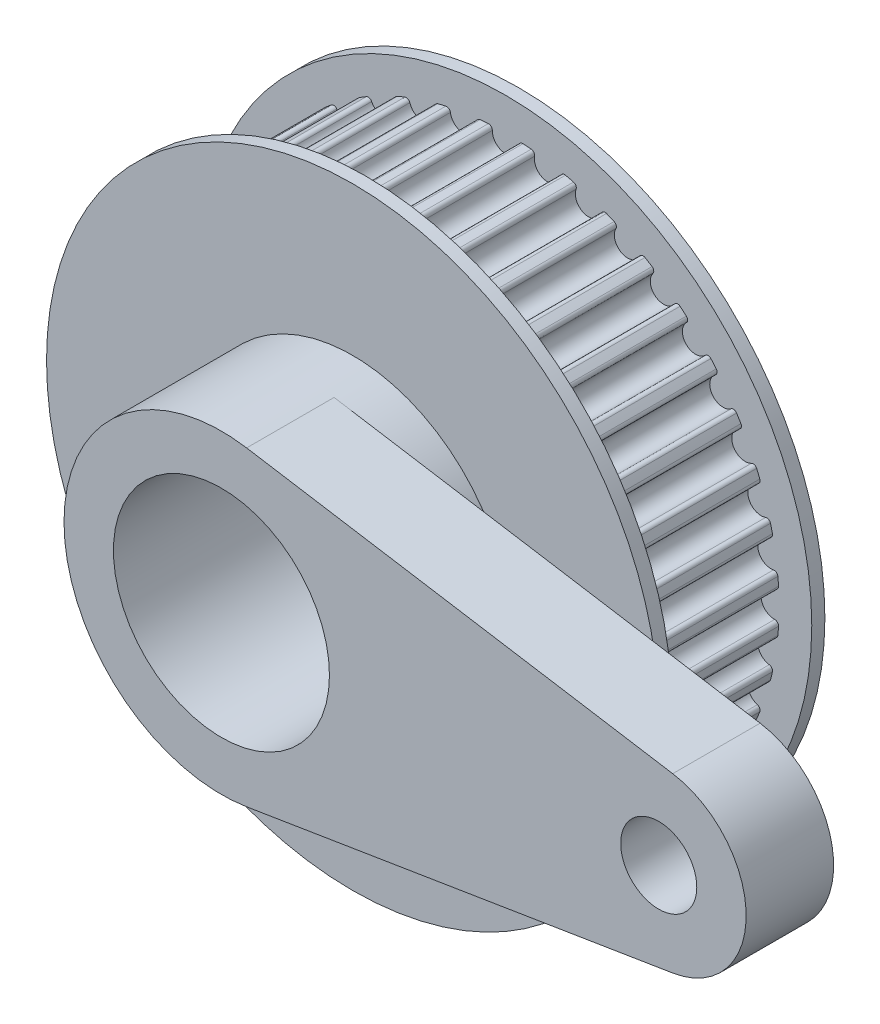
SolidWorks part; units mm, degrees
ref_plane "Front Plane" through (0, 0, 0) normal (0, 0, 1) x (1, 0, 0)
ref_plane "Top Plane" through (0, 0, 0) normal (0, 1, 0) x (1, 0, 0)
ref_plane "Right Plane" through (0, 0, 0) normal (1, 0, 0) x (0, 0, -1)
sketch "Sketch2" plane through (0, 0, 0) normal (0, 0, 1) x (1, 0, 0)
  line L0 (-22.12, 17.7681) -> (26.6, 9.8712)
  line L1 (-22.12, -17.7681) -> (26.6, -9.8712)
  arc A0 (-22.12, 17.7681) -> (-22.12, -17.7681) centre (-25, 0) ccw
  arc A1 (26.6, -9.8712) -> (26.6, 9.8712) centre (25, 0) ccw
  dimension "D1" = 36
  dimension "D2" = 20
  dimension "D3" = 50
  dimension "D4" = 25
extrude "Boss-Extrude1" add sketch "Sketch2" along normal blind 15
sketch "Sketch3" plane through (0, 0, 15) normal (0, 0, 1) x (1, 0, 0)
  circle A0 centre (-25, 0) radius 12.35
  circle A2 centre (25, 0) radius 4.35
  dimension "D1" = 24.7
  dimension "D2" = 8.7
extrude "Cut-Extrude1" cut sketch "Sketch3" against normal through all
sketch "Sketch4" plane through (0, 0, 0) normal (0, 0, -1) x (-1, 0, 0)
  line L0 (22.12, 17.7681) -> (-26.6, 9.8712)
  line L1 (-26.6, -9.8712) -> (22.12, -17.7681)
  arc A0 (22.12, 17.7681) -> (22.12, -17.7681) centre (25, 0) ccw
  arc A1 (-26.6, 9.8712) -> (-26.6, -9.8712) centre (-25, 0) ccw
extrude "Cut-Extrude2" cut sketch "Sketch4" against normal blind 5
sketch "Sketch5" plane through (0, 0, 15) normal (0, 0, 1) x (1, 0, 0)
  arc A2 (-25, 29.2) -> (-23.4754, 30.7585) centre (-25, 30.725) ccw
  arc A3 (-23.0182, 31.1971) -> (-23.4754, 30.7585) centre (-23.0455, 30.768) ccw
  arc A4 (-21.6942, 30.6183) -> (-20.4321, 28.8405) centre (-20.1936, 30.3467) ccw
  arc A5 (-21.6942, 30.6183) -> (-22.0771, 31.123) centre (-22.1173, 30.6949) ccw
  arc A6 (-22.0771, 31.123) -> (-23.0182, 31.1971) centre (-25, 0) ccw
  arc A7 (-20.4321, 28.8405) -> (-18.6824, 30.1413) centre (-20.1936, 30.3467) ccw
  arc A8 (-18.1623, 30.503) -> (-18.6824, 30.1413) centre (-18.2564, 30.0834) ccw
  arc A9 (-17.2444, 30.2826) -> (-18.1623, 30.503) centre (-25, 0) ccw
  arc A10 (-16.9451, 29.7242) -> (-17.2444, 30.2826) centre (-17.351, 29.8661) ccw
  arc A11 (-16.9451, 29.7242) -> (-15.9767, 27.7709) centre (-15.5055, 29.2212) ccw
  arc A12 (-15.9767, 27.7709) -> (-14.0451, 28.782) centre (-15.5055, 29.2212) ccw
  arc A13 (-13.4748, 29.0578) -> (-14.0451, 28.782) centre (-13.6333, 28.6581) ccw
  arc A14 (-12.6026, 28.6965) -> (-13.4748, 29.0578) centre (-25, 0) ccw
  arc A15 (-12.3944, 28.0982) -> (-12.6026, 28.6965) centre (-12.7731, 28.3018) ccw
  arc A16 (-12.3944, 28.0982) -> (-11.7435, 26.0174) centre (-11.0511, 27.3762) ccw
  arc A17 (-11.7435, 26.0174) -> (-9.6775, 26.7139) centre (-11.0511, 27.3762) ccw
  arc A18 (-9.071, 26.8971) -> (-9.6775, 26.7139) centre (-9.2901, 26.5271) ccw
  arc A19 (-8.2661, 26.4039) -> (-9.071, 26.8971) centre (-25, 0) ccw
  arc A20 (-8.154, 25.7803) -> (-8.2661, 26.4039) centre (-8.4963, 26.0407) ccw
  arc A21 (-8.154, 25.7803) -> (-7.8367, 23.6233) centre (-6.9403, 24.857) ccw
  arc A22 (-7.8367, 23.6233) -> (-5.6871, 23.988) centre (-6.9403, 24.857) ccw
  arc A23 (-5.0595, 24.0741) -> (-5.6871, 23.988) centre (-5.3338, 23.743) ccw
  arc A24 (-4.3416, 23.461) -> (-5.0595, 24.0741) centre (-25, 0) ccw
  arc A25 (-4.3285, 22.8276) -> (-4.3416, 23.461) centre (-4.6258, 23.1383) ccw
  arc A26 (-4.3285, 22.8276) -> (-4.3525, 20.6475) centre (-3.2741, 21.7259) ccw
  arc A27 (-4.3525, 20.6475) -> (-2.1724, 20.6715) centre (-3.2741, 21.7259) ccw
  arc A28 (-1.539, 20.6584) -> (-2.1724, 20.6715) centre (-1.8617, 20.3742) ccw
  arc A29 (-0.9259, 19.9405) -> (-1.539, 20.6584) centre (-25, 0) ccw
  arc A30 (-1.012, 19.3129) -> (-0.9259, 19.9405) centre (-1.257, 19.6662) ccw
  arc A31 (-1.012, 19.3129) -> (-1.3767, 17.1633) centre (-0.143, 18.0597) ccw
  arc A32 (-1.3767, 17.1633) -> (0.7803, 16.846) centre (-0.143, 18.0597) ccw
  arc A33 (1.4039, 16.7339) -> (0.7803, 16.846) centre (1.0407, 16.5037) ccw
  arc A34 (1.8971, 15.929) -> (1.4039, 16.7339) centre (-25, 0) ccw
  arc A35 (1.7139, 15.3225) -> (1.8971, 15.929) centre (1.5271, 15.7099) ccw
  arc A36 (1.7139, 15.3225) -> (1.0174, 13.2565) centre (2.3762, 13.9489) ccw
  arc A37 (1.0174, 13.2565) -> (3.0982, 12.6056) centre (2.3762, 13.9489) ccw
  arc A38 (3.6965, 12.3974) -> (3.0982, 12.6056) centre (3.3018, 12.2269) ccw
  arc A39 (4.0578, 11.5252) -> (3.6965, 12.3974) centre (-25, 0) ccw
  arc A40 (3.782, 10.9549) -> (4.0578, 11.5252) centre (3.6581, 11.3667) ccw
  arc A41 (3.782, 10.9549) -> (2.7709, 9.0233) centre (4.2212, 9.4945) ccw
  arc A42 (2.7709, 9.0233) -> (4.7242, 8.0549) centre (4.2212, 9.4945) ccw
  arc A43 (5.2826, 7.7556) -> (4.7242, 8.0549) centre (4.8661, 7.649) ccw
  arc A44 (5.503, 6.8377) -> (5.2826, 7.7556) centre (-25, 0) ccw
  arc A45 (5.1413, 6.3176) -> (5.503, 6.8377) centre (5.0834, 6.7436) ccw
  arc A46 (5.1413, 6.3176) -> (3.8405, 4.5679) centre (5.3467, 4.8064) ccw
  arc A47 (3.8405, 4.5679) -> (5.6183, 3.3058) centre (5.3467, 4.8064) ccw
  arc A48 (6.123, 2.9229) -> (5.6183, 3.3058) centre (5.6949, 2.8827) ccw
  arc A49 (6.1971, 1.9818) -> (6.123, 2.9229) centre (-25, 0) ccw
  arc A50 (5.7585, 1.5246) -> (6.1971, 1.9818) centre (5.768, 1.9545) ccw
  arc A51 (5.7585, 1.5246) -> (4.2, 0) centre (5.725, 0) ccw
  arc A52 (4.2, 0) -> (5.7585, -1.5246) centre (5.725, 0) ccw
  arc A53 (6.1971, -1.9818) -> (5.7585, -1.5246) centre (5.768, -1.9545) ccw
  arc A54 (6.123, -2.9229) -> (6.1971, -1.9818) centre (-25, 0) ccw
  arc A55 (5.6183, -3.3058) -> (6.123, -2.9229) centre (5.6949, -2.8827) ccw
  arc A56 (5.6183, -3.3058) -> (3.8405, -4.5679) centre (5.3467, -4.8064) ccw
  arc A57 (3.8405, -4.5679) -> (5.1413, -6.3176) centre (5.3467, -4.8064) ccw
  arc A58 (5.503, -6.8377) -> (5.1413, -6.3176) centre (5.0834, -6.7436) ccw
  arc A59 (5.2826, -7.7556) -> (5.503, -6.8377) centre (-25, 0) ccw
  arc A60 (4.7242, -8.0549) -> (5.2826, -7.7556) centre (4.8661, -7.649) ccw
  arc A61 (4.7242, -8.0549) -> (2.7709, -9.0233) centre (4.2212, -9.4945) ccw
  arc A62 (2.7709, -9.0233) -> (3.782, -10.9549) centre (4.2212, -9.4945) ccw
  arc A63 (4.0578, -11.5252) -> (3.782, -10.9549) centre (3.6581, -11.3667) ccw
  arc A64 (3.6965, -12.3974) -> (4.0578, -11.5252) centre (-25, 0) ccw
  arc A65 (3.0982, -12.6056) -> (3.6965, -12.3974) centre (3.3018, -12.2269) ccw
  arc A66 (3.0982, -12.6056) -> (1.0174, -13.2565) centre (2.3762, -13.9489) ccw
  arc A67 (1.0174, -13.2565) -> (1.7139, -15.3225) centre (2.3762, -13.9489) ccw
  arc A68 (1.8971, -15.929) -> (1.7139, -15.3225) centre (1.5271, -15.7099) ccw
  arc A69 (1.4039, -16.7339) -> (1.8971, -15.929) centre (-25, 0) ccw
  arc A70 (0.7803, -16.846) -> (1.4039, -16.7339) centre (1.0407, -16.5037) ccw
  arc A71 (0.7803, -16.846) -> (-1.3767, -17.1633) centre (-0.143, -18.0597) ccw
  arc A72 (-1.3767, -17.1633) -> (-1.012, -19.3129) centre (-0.143, -18.0597) ccw
  arc A73 (-0.9259, -19.9405) -> (-1.012, -19.3129) centre (-1.257, -19.6662) ccw
  arc A74 (-1.539, -20.6584) -> (-0.9259, -19.9405) centre (-25, 0) ccw
  arc A75 (-2.1724, -20.6715) -> (-1.539, -20.6584) centre (-1.8617, -20.3742) ccw
  arc A76 (-2.1724, -20.6715) -> (-4.3525, -20.6475) centre (-3.2741, -21.7259) ccw
  arc A77 (-4.3525, -20.6475) -> (-4.3285, -22.8276) centre (-3.2741, -21.7259) ccw
  arc A78 (-4.3416, -23.461) -> (-4.3285, -22.8276) centre (-4.6258, -23.1383) ccw
  arc A79 (-5.0595, -24.0741) -> (-4.3416, -23.461) centre (-25, 0) ccw
  arc A80 (-5.6871, -23.988) -> (-5.0595, -24.0741) centre (-5.3338, -23.743) ccw
  arc A81 (-5.6871, -23.988) -> (-7.8367, -23.6233) centre (-6.9403, -24.857) ccw
  arc A82 (-7.8367, -23.6233) -> (-8.154, -25.7803) centre (-6.9403, -24.857) ccw
  arc A83 (-8.2661, -26.4039) -> (-8.154, -25.7803) centre (-8.4963, -26.0407) ccw
  arc A84 (-9.071, -26.8971) -> (-8.2661, -26.4039) centre (-25, 0) ccw
  arc A85 (-9.6775, -26.7139) -> (-9.071, -26.8971) centre (-9.2901, -26.5271) ccw
  arc A86 (-9.6775, -26.7139) -> (-11.7435, -26.0174) centre (-11.0511, -27.3762) ccw
  arc A87 (-11.7435, -26.0174) -> (-12.3944, -28.0982) centre (-11.0511, -27.3762) ccw
  arc A88 (-12.6026, -28.6965) -> (-12.3944, -28.0982) centre (-12.7731, -28.3018) ccw
  arc A89 (-13.4748, -29.0578) -> (-12.6026, -28.6965) centre (-25, 0) ccw
  arc A90 (-14.0451, -28.782) -> (-13.4748, -29.0578) centre (-13.6333, -28.6581) ccw
  arc A91 (-14.0451, -28.782) -> (-15.9767, -27.7709) centre (-15.5055, -29.2212) ccw
  arc A92 (-15.9767, -27.7709) -> (-16.9451, -29.7242) centre (-15.5055, -29.2212) ccw
  arc A93 (-17.2444, -30.2826) -> (-16.9451, -29.7242) centre (-17.351, -29.8661) ccw
  arc A94 (-18.1623, -30.503) -> (-17.2444, -30.2826) centre (-25, 0) ccw
  arc A95 (-18.6824, -30.1413) -> (-18.1623, -30.503) centre (-18.2564, -30.0834) ccw
  arc A96 (-18.6824, -30.1413) -> (-20.4321, -28.8405) centre (-20.1936, -30.3467) ccw
  arc A97 (-20.4321, -28.8405) -> (-21.6942, -30.6183) centre (-20.1936, -30.3467) ccw
  arc A98 (-22.0771, -31.123) -> (-21.6942, -30.6183) centre (-22.1173, -30.6949) ccw
  arc A99 (-23.0182, -31.1971) -> (-22.0771, -31.123) centre (-25, 0) ccw
  arc A100 (-23.4754, -30.7585) -> (-23.0182, -31.1971) centre (-23.0455, -30.768) ccw
  arc A101 (-23.4754, -30.7585) -> (-25, -29.2) centre (-25, -30.725) ccw
  arc A102 (-25, -29.2) -> (-26.5246, -30.7585) centre (-25, -30.725) ccw
  arc A103 (-26.9818, -31.1971) -> (-26.5246, -30.7585) centre (-26.9545, -30.768) ccw
  arc A104 (-27.9229, -31.123) -> (-26.9818, -31.1971) centre (-25, 0) ccw
  arc A105 (-28.3058, -30.6183) -> (-27.9229, -31.123) centre (-27.8827, -30.6949) ccw
  arc A106 (-28.3058, -30.6183) -> (-29.5679, -28.8405) centre (-29.8064, -30.3467) ccw
  arc A107 (-29.5679, -28.8405) -> (-31.3176, -30.1413) centre (-29.8064, -30.3467) ccw
  arc A108 (-31.8377, -30.503) -> (-31.3176, -30.1413) centre (-31.7436, -30.0834) ccw
  arc A109 (-32.7556, -30.2826) -> (-31.8377, -30.503) centre (-25, 0) ccw
  arc A110 (-33.0549, -29.7242) -> (-32.7556, -30.2826) centre (-32.649, -29.8661) ccw
  arc A111 (-33.0549, -29.7242) -> (-34.0233, -27.7709) centre (-34.4945, -29.2212) ccw
  arc A112 (-34.0233, -27.7709) -> (-35.9549, -28.782) centre (-34.4945, -29.2212) ccw
  arc A113 (-36.5252, -29.0578) -> (-35.9549, -28.782) centre (-36.3667, -28.6581) ccw
  arc A114 (-37.3974, -28.6965) -> (-36.5252, -29.0578) centre (-25, 0) ccw
  arc A115 (-37.6056, -28.0982) -> (-37.3974, -28.6965) centre (-37.2269, -28.3018) ccw
  arc A116 (-37.6056, -28.0982) -> (-38.2565, -26.0174) centre (-38.9489, -27.3762) ccw
  arc A117 (-38.2565, -26.0174) -> (-40.3225, -26.7139) centre (-38.9489, -27.3762) ccw
  arc A118 (-40.929, -26.8971) -> (-40.3225, -26.7139) centre (-40.7099, -26.5271) ccw
  arc A119 (-41.7339, -26.4039) -> (-40.929, -26.8971) centre (-25, 0) ccw
  arc A120 (-41.846, -25.7803) -> (-41.7339, -26.4039) centre (-41.5037, -26.0407) ccw
  arc A121 (-41.846, -25.7803) -> (-42.1633, -23.6233) centre (-43.0597, -24.857) ccw
  arc A122 (-42.1633, -23.6233) -> (-44.3129, -23.988) centre (-43.0597, -24.857) ccw
  arc A123 (-44.9405, -24.0741) -> (-44.3129, -23.988) centre (-44.6662, -23.743) ccw
  arc A124 (-45.6584, -23.461) -> (-44.9405, -24.0741) centre (-25, 0) ccw
  arc A125 (-45.6715, -22.8276) -> (-45.6584, -23.461) centre (-45.3742, -23.1383) ccw
  arc A126 (-45.6715, -22.8276) -> (-45.6475, -20.6475) centre (-46.7259, -21.7259) ccw
  arc A127 (-45.6475, -20.6475) -> (-47.8276, -20.6715) centre (-46.7259, -21.7259) ccw
  arc A128 (-48.461, -20.6584) -> (-47.8276, -20.6715) centre (-48.1383, -20.3742) ccw
  arc A129 (-49.0741, -19.9405) -> (-48.461, -20.6584) centre (-25, 0) ccw
  arc A130 (-48.988, -19.3129) -> (-49.0741, -19.9405) centre (-48.743, -19.6662) ccw
  arc A131 (-48.988, -19.3129) -> (-48.6233, -17.1633) centre (-49.857, -18.0597) ccw
  arc A132 (-48.6233, -17.1633) -> (-50.7803, -16.846) centre (-49.857, -18.0597) ccw
  arc A133 (-51.4039, -16.7339) -> (-50.7803, -16.846) centre (-51.0407, -16.5037) ccw
  arc A134 (-51.8971, -15.929) -> (-51.4039, -16.7339) centre (-25, 0) ccw
  arc A135 (-51.7139, -15.3225) -> (-51.8971, -15.929) centre (-51.5271, -15.7099) ccw
  arc A136 (-51.7139, -15.3225) -> (-51.0174, -13.2565) centre (-52.3762, -13.9489) ccw
  arc A137 (-51.0174, -13.2565) -> (-53.0982, -12.6056) centre (-52.3762, -13.9489) ccw
  arc A138 (-53.6965, -12.3974) -> (-53.0982, -12.6056) centre (-53.3018, -12.2269) ccw
  arc A139 (-54.0578, -11.5252) -> (-53.6965, -12.3974) centre (-25, 0) ccw
  arc A140 (-53.782, -10.9549) -> (-54.0578, -11.5252) centre (-53.6581, -11.3667) ccw
  arc A141 (-53.782, -10.9549) -> (-52.7709, -9.0233) centre (-54.2212, -9.4945) ccw
  arc A142 (-52.7709, -9.0233) -> (-54.7242, -8.0549) centre (-54.2212, -9.4945) ccw
  arc A143 (-55.2826, -7.7556) -> (-54.7242, -8.0549) centre (-54.8661, -7.649) ccw
  arc A144 (-55.503, -6.8377) -> (-55.2826, -7.7556) centre (-25, 0) ccw
  arc A145 (-55.1413, -6.3176) -> (-55.503, -6.8377) centre (-55.0834, -6.7436) ccw
  arc A146 (-55.1413, -6.3176) -> (-53.8405, -4.5679) centre (-55.3467, -4.8064) ccw
  arc A147 (-53.8405, -4.5679) -> (-55.6183, -3.3058) centre (-55.3467, -4.8064) ccw
  arc A148 (-56.123, -2.9229) -> (-55.6183, -3.3058) centre (-55.6949, -2.8827) ccw
  arc A149 (-56.1971, -1.9818) -> (-56.123, -2.9229) centre (-25, 0) ccw
  arc A150 (-55.7585, -1.5246) -> (-56.1971, -1.9818) centre (-55.768, -1.9545) ccw
  arc A151 (-55.7585, -1.5246) -> (-54.2, 0) centre (-55.725, 0) ccw
  arc A152 (-54.2, 0) -> (-55.7585, 1.5246) centre (-55.725, 0) ccw
  arc A153 (-56.1971, 1.9818) -> (-55.7585, 1.5246) centre (-55.768, 1.9545) ccw
  arc A154 (-56.123, 2.9229) -> (-56.1971, 1.9818) centre (-25, 0) ccw
  arc A155 (-55.6183, 3.3058) -> (-56.123, 2.9229) centre (-55.6949, 2.8827) ccw
  arc A156 (-55.6183, 3.3058) -> (-53.8405, 4.5679) centre (-55.3467, 4.8064) ccw
  arc A157 (-53.8405, 4.5679) -> (-55.1413, 6.3176) centre (-55.3467, 4.8064) ccw
  arc A158 (-55.503, 6.8377) -> (-55.1413, 6.3176) centre (-55.0834, 6.7436) ccw
  arc A159 (-55.2826, 7.7556) -> (-55.503, 6.8377) centre (-25, 0) ccw
  arc A160 (-54.7242, 8.0549) -> (-55.2826, 7.7556) centre (-54.8661, 7.649) ccw
  arc A161 (-54.7242, 8.0549) -> (-52.7709, 9.0233) centre (-54.2212, 9.4945) ccw
  arc A162 (-52.7709, 9.0233) -> (-53.782, 10.9549) centre (-54.2212, 9.4945) ccw
  arc A163 (-54.0578, 11.5252) -> (-53.782, 10.9549) centre (-53.6581, 11.3667) ccw
  arc A164 (-53.6965, 12.3974) -> (-54.0578, 11.5252) centre (-25, 0) ccw
  arc A165 (-53.0982, 12.6056) -> (-53.6965, 12.3974) centre (-53.3018, 12.2269) ccw
  arc A166 (-53.0982, 12.6056) -> (-51.0174, 13.2565) centre (-52.3762, 13.9489) ccw
  arc A167 (-51.0174, 13.2565) -> (-51.7139, 15.3225) centre (-52.3762, 13.9489) ccw
  arc A168 (-51.8971, 15.929) -> (-51.7139, 15.3225) centre (-51.5271, 15.7099) ccw
  arc A169 (-51.4039, 16.7339) -> (-51.8971, 15.929) centre (-25, 0) ccw
  arc A170 (-50.7803, 16.846) -> (-51.4039, 16.7339) centre (-51.0407, 16.5037) ccw
  arc A171 (-50.7803, 16.846) -> (-48.6233, 17.1633) centre (-49.857, 18.0597) ccw
  arc A172 (-48.6233, 17.1633) -> (-48.988, 19.3129) centre (-49.857, 18.0597) ccw
  arc A173 (-49.0741, 19.9405) -> (-48.988, 19.3129) centre (-48.743, 19.6662) ccw
  arc A174 (-48.461, 20.6584) -> (-49.0741, 19.9405) centre (-25, 0) ccw
  arc A175 (-47.8276, 20.6715) -> (-48.461, 20.6584) centre (-48.1383, 20.3742) ccw
  arc A176 (-47.8276, 20.6715) -> (-45.6475, 20.6475) centre (-46.7259, 21.7259) ccw
  arc A177 (-45.6475, 20.6475) -> (-45.6715, 22.8276) centre (-46.7259, 21.7259) ccw
  arc A178 (-45.6584, 23.461) -> (-45.6715, 22.8276) centre (-45.3742, 23.1383) ccw
  arc A179 (-44.9405, 24.0741) -> (-45.6584, 23.461) centre (-25, 0) ccw
  arc A180 (-44.3129, 23.988) -> (-44.9405, 24.0741) centre (-44.6662, 23.743) ccw
  arc A181 (-44.3129, 23.988) -> (-42.1633, 23.6233) centre (-43.0597, 24.857) ccw
  arc A182 (-42.1633, 23.6233) -> (-41.846, 25.7803) centre (-43.0597, 24.857) ccw
  arc A183 (-41.7339, 26.4039) -> (-41.846, 25.7803) centre (-41.5037, 26.0407) ccw
  arc A184 (-40.929, 26.8971) -> (-41.7339, 26.4039) centre (-25, 0) ccw
  arc A185 (-40.3225, 26.7139) -> (-40.929, 26.8971) centre (-40.7099, 26.5271) ccw
  arc A186 (-40.3225, 26.7139) -> (-38.2565, 26.0174) centre (-38.9489, 27.3762) ccw
  arc A187 (-38.2565, 26.0174) -> (-37.6056, 28.0982) centre (-38.9489, 27.3762) ccw
  arc A188 (-37.3974, 28.6965) -> (-37.6056, 28.0982) centre (-37.2269, 28.3018) ccw
  arc A189 (-36.5252, 29.0578) -> (-37.3974, 28.6965) centre (-25, 0) ccw
  arc A190 (-35.9549, 28.782) -> (-36.5252, 29.0578) centre (-36.3667, 28.6581) ccw
  arc A191 (-35.9549, 28.782) -> (-34.0233, 27.7709) centre (-34.4945, 29.2212) ccw
  arc A192 (-34.0233, 27.7709) -> (-33.0549, 29.7242) centre (-34.4945, 29.2212) ccw
  arc A193 (-32.7556, 30.2826) -> (-33.0549, 29.7242) centre (-32.649, 29.8661) ccw
  arc A194 (-31.8377, 30.503) -> (-32.7556, 30.2826) centre (-25, 0) ccw
  arc A195 (-31.3176, 30.1413) -> (-31.8377, 30.503) centre (-31.7436, 30.0834) ccw
  arc A196 (-31.3176, 30.1413) -> (-29.5679, 28.8405) centre (-29.8064, 30.3467) ccw
  arc A197 (-29.5679, 28.8405) -> (-28.3058, 30.6183) centre (-29.8064, 30.3467) ccw
  arc A198 (-27.9229, 31.123) -> (-28.3058, 30.6183) centre (-27.8827, 30.6949) ccw
  arc A199 (-26.9818, 31.1971) -> (-27.9229, 31.123) centre (-25, 0) ccw
  arc A200 (-26.5246, 30.7585) -> (-26.9818, 31.1971) centre (-26.9545, 30.768) ccw
  arc A201 (-26.5246, 30.7585) -> (-25, 29.2) centre (-25, 30.725) ccw
  point P407 (-25, 0)
  dimension "D1" = 40
  dimension "D4" = 3.05
  dimension "D5" = 0.86
  dimension "D6" = 3.05
  dimension "D7" = 0.86
sketch "Sketch6" plane through (0, 0, 0) normal (0, 0, -1) x (-1, 0, 0)
  circle A0 centre (25, 0) radius 35
  dimension "D1" = 70
extrude "Boss-Extrude2" add sketch "Sketch6" along normal blind 1.5
sketch "Sketch7" plane through (0, 0, -1.5) normal (0, 0, -1) x (-1, 0, 0)
  circle A1 centre (25, 0) radius 35
  circle A2 centre (25, 0) radius 35
  arc A202 (47.8276, -20.6715) -> (45.6475, -20.6475) centre (46.7259, -21.7259) ccw
  arc A203 (47.8276, -20.6715) -> (48.461, -20.6584) centre (48.1383, -20.3742) ccw
  arc A204 (48.461, -20.6584) -> (49.0741, -19.9405) centre (25, 0) ccw
  arc A205 (49.0741, -19.9405) -> (48.988, -19.3129) centre (48.743, -19.6662) ccw
  arc A206 (48.6233, -17.1633) -> (48.988, -19.3129) centre (49.857, -18.0597) ccw
  arc A207 (50.7803, -16.846) -> (48.6233, -17.1633) centre (49.857, -18.0597) ccw
  arc A208 (50.7803, -16.846) -> (51.4039, -16.7339) centre (51.0407, -16.5037) ccw
  arc A209 (51.4039, -16.7339) -> (51.8971, -15.929) centre (25, 0) ccw
  arc A210 (51.8971, -15.929) -> (51.7139, -15.3225) centre (51.5271, -15.7099) ccw
  arc A211 (51.0174, -13.2565) -> (51.7139, -15.3225) centre (52.3762, -13.9489) ccw
  arc A212 (53.0982, -12.6056) -> (51.0174, -13.2565) centre (52.3762, -13.9489) ccw
  arc A213 (53.0982, -12.6056) -> (53.6965, -12.3974) centre (53.3018, -12.2269) ccw
  arc A214 (53.6965, -12.3974) -> (54.0578, -11.5252) centre (25, 0) ccw
  arc A215 (54.0578, -11.5252) -> (53.782, -10.9549) centre (53.6581, -11.3667) ccw
  arc A216 (52.7709, -9.0233) -> (53.782, -10.9549) centre (54.2212, -9.4945) ccw
  arc A217 (54.7242, -8.0549) -> (52.7709, -9.0233) centre (54.2212, -9.4945) ccw
  arc A218 (54.7242, -8.0549) -> (55.2826, -7.7556) centre (54.8661, -7.649) ccw
  arc A219 (55.2826, -7.7556) -> (55.503, -6.8377) centre (25, 0) ccw
  arc A220 (55.503, -6.8377) -> (55.1413, -6.3176) centre (55.0834, -6.7436) ccw
  arc A221 (53.8405, -4.5679) -> (55.1413, -6.3176) centre (55.3467, -4.8064) ccw
  arc A222 (55.6183, -3.3058) -> (53.8405, -4.5679) centre (55.3467, -4.8064) ccw
  arc A223 (55.6183, -3.3058) -> (56.123, -2.9229) centre (55.6949, -2.8827) ccw
  arc A224 (56.123, -2.9229) -> (56.1971, -1.9818) centre (25, 0) ccw
  arc A225 (56.1971, -1.9818) -> (55.7585, -1.5246) centre (55.768, -1.9545) ccw
  arc A226 (54.2, 0) -> (55.7585, -1.5246) centre (55.725, 0) ccw
  arc A227 (55.7585, 1.5246) -> (54.2, 0) centre (55.725, 0) ccw
  arc A228 (55.7585, 1.5246) -> (56.1971, 1.9818) centre (55.768, 1.9545) ccw
  arc A229 (56.1971, 1.9818) -> (56.123, 2.9229) centre (25, 0) ccw
  arc A230 (56.123, 2.9229) -> (55.6183, 3.3058) centre (55.6949, 2.8827) ccw
  arc A231 (53.8405, 4.5679) -> (55.6183, 3.3058) centre (55.3467, 4.8064) ccw
  arc A232 (55.1413, 6.3176) -> (53.8405, 4.5679) centre (55.3467, 4.8064) ccw
  arc A233 (55.1413, 6.3176) -> (55.503, 6.8377) centre (55.0834, 6.7436) ccw
  arc A234 (55.503, 6.8377) -> (55.2826, 7.7556) centre (25, 0) ccw
  arc A235 (55.2826, 7.7556) -> (54.7242, 8.0549) centre (54.8661, 7.649) ccw
  arc A236 (52.7709, 9.0233) -> (54.7242, 8.0549) centre (54.2212, 9.4945) ccw
  arc A237 (53.782, 10.9549) -> (52.7709, 9.0233) centre (54.2212, 9.4945) ccw
  arc A238 (53.782, 10.9549) -> (54.0578, 11.5252) centre (53.6581, 11.3667) ccw
  arc A239 (54.0578, 11.5252) -> (53.6965, 12.3974) centre (25, 0) ccw
  arc A240 (53.6965, 12.3974) -> (53.0982, 12.6056) centre (53.3018, 12.2269) ccw
  arc A241 (51.0174, 13.2565) -> (53.0982, 12.6056) centre (52.3762, 13.9489) ccw
  arc A242 (51.7139, 15.3225) -> (51.0174, 13.2565) centre (52.3762, 13.9489) ccw
  arc A243 (51.7139, 15.3225) -> (51.8971, 15.929) centre (51.5271, 15.7099) ccw
  arc A244 (51.8971, 15.929) -> (51.4039, 16.7339) centre (25, 0) ccw
  arc A245 (51.4039, 16.7339) -> (50.7803, 16.846) centre (51.0407, 16.5037) ccw
  arc A246 (48.6233, 17.1633) -> (50.7803, 16.846) centre (49.857, 18.0597) ccw
  arc A247 (48.988, 19.3129) -> (48.6233, 17.1633) centre (49.857, 18.0597) ccw
  arc A248 (48.988, 19.3129) -> (49.0741, 19.9405) centre (48.743, 19.6662) ccw
  arc A249 (49.0741, 19.9405) -> (48.461, 20.6584) centre (25, 0) ccw
  arc A250 (48.461, 20.6584) -> (47.8276, 20.6715) centre (48.1383, 20.3742) ccw
  arc A251 (45.6475, 20.6475) -> (47.8276, 20.6715) centre (46.7259, 21.7259) ccw
  arc A252 (45.6715, 22.8276) -> (45.6475, 20.6475) centre (46.7259, 21.7259) ccw
  arc A253 (45.6715, 22.8276) -> (45.6584, 23.461) centre (45.3742, 23.1383) ccw
  arc A254 (45.6584, 23.461) -> (44.9405, 24.0741) centre (25, 0) ccw
  arc A255 (44.9405, 24.0741) -> (44.3129, 23.988) centre (44.6662, 23.743) ccw
  arc A256 (42.1633, 23.6233) -> (44.3129, 23.988) centre (43.0597, 24.857) ccw
  arc A257 (41.846, 25.7803) -> (42.1633, 23.6233) centre (43.0597, 24.857) ccw
  arc A258 (41.846, 25.7803) -> (41.7339, 26.4039) centre (41.5037, 26.0407) ccw
  arc A259 (41.7339, 26.4039) -> (40.929, 26.8971) centre (25, 0) ccw
  arc A260 (40.929, 26.8971) -> (40.3225, 26.7139) centre (40.7099, 26.5271) ccw
  arc A261 (38.2565, 26.0174) -> (40.3225, 26.7139) centre (38.9489, 27.3762) ccw
  arc A262 (37.6056, 28.0982) -> (38.2565, 26.0174) centre (38.9489, 27.3762) ccw
  arc A263 (37.6056, 28.0982) -> (37.3974, 28.6965) centre (37.2269, 28.3018) ccw
  arc A264 (37.3974, 28.6965) -> (36.5252, 29.0578) centre (25, 0) ccw
  arc A265 (36.5252, 29.0578) -> (35.9549, 28.782) centre (36.3667, 28.6581) ccw
  arc A266 (34.0233, 27.7709) -> (35.9549, 28.782) centre (34.4945, 29.2212) ccw
  arc A267 (33.0549, 29.7242) -> (34.0233, 27.7709) centre (34.4945, 29.2212) ccw
  arc A268 (33.0549, 29.7242) -> (32.7556, 30.2826) centre (32.649, 29.8661) ccw
  arc A269 (32.7556, 30.2826) -> (31.8377, 30.503) centre (25, 0) ccw
  arc A270 (31.8377, 30.503) -> (31.3176, 30.1413) centre (31.7436, 30.0834) ccw
  arc A271 (29.5679, 28.8405) -> (31.3176, 30.1413) centre (29.8064, 30.3467) ccw
  arc A272 (28.3058, 30.6183) -> (29.5679, 28.8405) centre (29.8064, 30.3467) ccw
  arc A273 (28.3058, 30.6183) -> (27.9229, 31.123) centre (27.8827, 30.6949) ccw
  arc A274 (27.9229, 31.123) -> (26.9818, 31.1971) centre (25, 0) ccw
  arc A275 (26.9818, 31.1971) -> (26.5246, 30.7585) centre (26.9545, 30.768) ccw
  arc A276 (25, 29.2) -> (26.5246, 30.7585) centre (25, 30.725) ccw
  arc A277 (23.4754, 30.7585) -> (25, 29.2) centre (25, 30.725) ccw
  arc A278 (23.4754, 30.7585) -> (23.0182, 31.1971) centre (23.0455, 30.768) ccw
  arc A279 (23.0182, 31.1971) -> (22.0771, 31.123) centre (25, 0) ccw
  arc A280 (22.0771, 31.123) -> (21.6942, 30.6183) centre (22.1173, 30.6949) ccw
  arc A281 (20.4321, 28.8405) -> (21.6942, 30.6183) centre (20.1936, 30.3467) ccw
  arc A282 (18.6824, 30.1413) -> (20.4321, 28.8405) centre (20.1936, 30.3467) ccw
  arc A283 (18.6824, 30.1413) -> (18.1623, 30.503) centre (18.2564, 30.0834) ccw
  arc A284 (18.1623, 30.503) -> (17.2444, 30.2826) centre (25, 0) ccw
  arc A285 (17.2444, 30.2826) -> (16.9451, 29.7242) centre (17.351, 29.8661) ccw
  arc A286 (15.9767, 27.7709) -> (16.9451, 29.7242) centre (15.5055, 29.2212) ccw
  arc A287 (14.0451, 28.782) -> (15.9767, 27.7709) centre (15.5055, 29.2212) ccw
  arc A288 (14.0451, 28.782) -> (13.4748, 29.0578) centre (13.6333, 28.6581) ccw
  arc A289 (13.4748, 29.0578) -> (12.6026, 28.6965) centre (25, 0) ccw
  arc A290 (12.6026, 28.6965) -> (12.3944, 28.0982) centre (12.7731, 28.3018) ccw
  arc A291 (11.7435, 26.0174) -> (12.3944, 28.0982) centre (11.0511, 27.3762) ccw
  arc A292 (9.6775, 26.7139) -> (11.7435, 26.0174) centre (11.0511, 27.3762) ccw
  arc A293 (9.6775, 26.7139) -> (9.071, 26.8971) centre (9.2901, 26.5271) ccw
  arc A294 (9.071, 26.8971) -> (8.2661, 26.4039) centre (25, 0) ccw
  arc A295 (8.2661, 26.4039) -> (8.154, 25.7803) centre (8.4963, 26.0407) ccw
  arc A296 (7.8367, 23.6233) -> (8.154, 25.7803) centre (6.9403, 24.857) ccw
  arc A297 (5.6871, 23.988) -> (7.8367, 23.6233) centre (6.9403, 24.857) ccw
  arc A298 (5.6871, 23.988) -> (5.0595, 24.0741) centre (5.3338, 23.743) ccw
  arc A299 (5.0595, 24.0741) -> (4.3416, 23.461) centre (25, 0) ccw
  arc A300 (4.3416, 23.461) -> (4.3285, 22.8276) centre (4.6258, 23.1383) ccw
  arc A301 (4.3525, 20.6475) -> (4.3285, 22.8276) centre (3.2741, 21.7259) ccw
  arc A302 (2.1724, 20.6715) -> (4.3525, 20.6475) centre (3.2741, 21.7259) ccw
  arc A303 (2.1724, 20.6715) -> (1.539, 20.6584) centre (1.8617, 20.3742) ccw
  arc A304 (1.539, 20.6584) -> (0.9259, 19.9405) centre (25, 0) ccw
  arc A305 (0.9259, 19.9405) -> (1.012, 19.3129) centre (1.257, 19.6662) ccw
  arc A306 (1.3767, 17.1633) -> (1.012, 19.3129) centre (0.143, 18.0597) ccw
  arc A307 (-0.7803, 16.846) -> (1.3767, 17.1633) centre (0.143, 18.0597) ccw
  arc A308 (-0.7803, 16.846) -> (-1.4039, 16.7339) centre (-1.0407, 16.5037) ccw
  arc A309 (-1.4039, 16.7339) -> (-1.8971, 15.929) centre (25, 0) ccw
  arc A310 (-1.8971, 15.929) -> (-1.7139, 15.3225) centre (-1.5271, 15.7099) ccw
  arc A311 (-1.0174, 13.2565) -> (-1.7139, 15.3225) centre (-2.3762, 13.9489) ccw
  arc A312 (-3.0982, 12.6056) -> (-1.0174, 13.2565) centre (-2.3762, 13.9489) ccw
  arc A313 (-3.0982, 12.6056) -> (-3.6965, 12.3974) centre (-3.3018, 12.2269) ccw
  arc A314 (-3.6965, 12.3974) -> (-4.0578, 11.5252) centre (25, 0) ccw
  arc A315 (-4.0578, 11.5252) -> (-3.782, 10.9549) centre (-3.6581, 11.3667) ccw
  arc A316 (-2.7709, 9.0233) -> (-3.782, 10.9549) centre (-4.2212, 9.4945) ccw
  arc A317 (-4.7242, 8.0549) -> (-2.7709, 9.0233) centre (-4.2212, 9.4945) ccw
  arc A318 (-4.7242, 8.0549) -> (-5.2826, 7.7556) centre (-4.8661, 7.649) ccw
  arc A319 (-5.2826, 7.7556) -> (-5.503, 6.8377) centre (25, 0) ccw
  arc A320 (-5.503, 6.8377) -> (-5.1413, 6.3176) centre (-5.0834, 6.7436) ccw
  arc A321 (-3.8405, 4.5679) -> (-5.1413, 6.3176) centre (-5.3467, 4.8064) ccw
  arc A322 (-5.6183, 3.3058) -> (-3.8405, 4.5679) centre (-5.3467, 4.8064) ccw
  arc A323 (-5.6183, 3.3058) -> (-6.123, 2.9229) centre (-5.6949, 2.8827) ccw
  arc A324 (-6.123, 2.9229) -> (-6.1971, 1.9818) centre (25, 0) ccw
  arc A325 (-6.1971, 1.9818) -> (-5.7585, 1.5246) centre (-5.768, 1.9545) ccw
  arc A326 (-4.2, 0) -> (-5.7585, 1.5246) centre (-5.725, 0) ccw
  arc A327 (-5.7585, -1.5246) -> (-4.2, 0) centre (-5.725, 0) ccw
  arc A328 (-5.7585, -1.5246) -> (-6.1971, -1.9818) centre (-5.768, -1.9545) ccw
  arc A329 (-6.1971, -1.9818) -> (-6.123, -2.9229) centre (25, 0) ccw
  arc A330 (-6.123, -2.9229) -> (-5.6183, -3.3058) centre (-5.6949, -2.8827) ccw
  arc A331 (-3.8405, -4.5679) -> (-5.6183, -3.3058) centre (-5.3467, -4.8064) ccw
  arc A332 (-5.1413, -6.3176) -> (-3.8405, -4.5679) centre (-5.3467, -4.8064) ccw
  arc A333 (-5.1413, -6.3176) -> (-5.503, -6.8377) centre (-5.0834, -6.7436) ccw
  arc A334 (-5.503, -6.8377) -> (-5.2826, -7.7556) centre (25, 0) ccw
  arc A335 (-5.2826, -7.7556) -> (-4.7242, -8.0549) centre (-4.8661, -7.649) ccw
  arc A336 (-2.7709, -9.0233) -> (-4.7242, -8.0549) centre (-4.2212, -9.4945) ccw
  arc A337 (-3.782, -10.9549) -> (-2.7709, -9.0233) centre (-4.2212, -9.4945) ccw
  arc A338 (-3.782, -10.9549) -> (-4.0578, -11.5252) centre (-3.6581, -11.3667) ccw
  arc A339 (-4.0578, -11.5252) -> (-3.6965, -12.3974) centre (25, 0) ccw
  arc A340 (-3.6965, -12.3974) -> (-3.0982, -12.6056) centre (-3.3018, -12.2269) ccw
  arc A341 (-1.0174, -13.2565) -> (-3.0982, -12.6056) centre (-2.3762, -13.9489) ccw
  arc A342 (-1.7139, -15.3225) -> (-1.0174, -13.2565) centre (-2.3762, -13.9489) ccw
  arc A343 (-1.7139, -15.3225) -> (-1.8971, -15.929) centre (-1.5271, -15.7099) ccw
  arc A344 (-1.8971, -15.929) -> (-1.4039, -16.7339) centre (25, 0) ccw
  arc A345 (-1.4039, -16.7339) -> (-0.7803, -16.846) centre (-1.0407, -16.5037) ccw
  arc A346 (1.3767, -17.1633) -> (-0.7803, -16.846) centre (0.143, -18.0597) ccw
  arc A347 (1.012, -19.3129) -> (1.3767, -17.1633) centre (0.143, -18.0597) ccw
  arc A348 (1.012, -19.3129) -> (0.9259, -19.9405) centre (1.257, -19.6662) ccw
  arc A349 (0.9259, -19.9405) -> (1.539, -20.6584) centre (25, 0) ccw
  arc A350 (1.539, -20.6584) -> (2.1724, -20.6715) centre (1.8617, -20.3742) ccw
  arc A351 (4.3525, -20.6475) -> (2.1724, -20.6715) centre (3.2741, -21.7259) ccw
  arc A352 (4.3285, -22.8276) -> (4.3525, -20.6475) centre (3.2741, -21.7259) ccw
  arc A353 (4.3285, -22.8276) -> (4.3416, -23.461) centre (4.6258, -23.1383) ccw
  arc A354 (4.3416, -23.461) -> (5.0595, -24.0741) centre (25, 0) ccw
  arc A355 (5.0595, -24.0741) -> (5.6871, -23.988) centre (5.3338, -23.743) ccw
  arc A356 (7.8367, -23.6233) -> (5.6871, -23.988) centre (6.9403, -24.857) ccw
  arc A357 (8.154, -25.7803) -> (7.8367, -23.6233) centre (6.9403, -24.857) ccw
  arc A358 (8.154, -25.7803) -> (8.2661, -26.4039) centre (8.4963, -26.0407) ccw
  arc A359 (8.2661, -26.4039) -> (9.071, -26.8971) centre (25, 0) ccw
  arc A360 (9.071, -26.8971) -> (9.6775, -26.7139) centre (9.2901, -26.5271) ccw
  arc A361 (11.7435, -26.0174) -> (9.6775, -26.7139) centre (11.0511, -27.3762) ccw
  arc A362 (12.3944, -28.0982) -> (11.7435, -26.0174) centre (11.0511, -27.3762) ccw
  arc A363 (12.3944, -28.0982) -> (12.6026, -28.6965) centre (12.7731, -28.3018) ccw
  arc A364 (12.6026, -28.6965) -> (13.4748, -29.0578) centre (25, 0) ccw
  arc A365 (13.4748, -29.0578) -> (14.0451, -28.782) centre (13.6333, -28.6581) ccw
  arc A366 (15.9767, -27.7709) -> (14.0451, -28.782) centre (15.5055, -29.2212) ccw
  arc A367 (16.9451, -29.7242) -> (15.9767, -27.7709) centre (15.5055, -29.2212) ccw
  arc A368 (16.9451, -29.7242) -> (17.2444, -30.2826) centre (17.351, -29.8661) ccw
  arc A369 (17.2444, -30.2826) -> (18.1623, -30.503) centre (25, 0) ccw
  arc A370 (18.1623, -30.503) -> (18.6824, -30.1413) centre (18.2564, -30.0834) ccw
  arc A371 (20.4321, -28.8405) -> (18.6824, -30.1413) centre (20.1936, -30.3467) ccw
  arc A372 (21.6942, -30.6183) -> (20.4321, -28.8405) centre (20.1936, -30.3467) ccw
  arc A373 (21.6942, -30.6183) -> (22.0771, -31.123) centre (22.1173, -30.6949) ccw
  arc A374 (22.0771, -31.123) -> (23.0182, -31.1971) centre (25, 0) ccw
  arc A375 (23.0182, -31.1971) -> (23.4754, -30.7585) centre (23.0455, -30.768) ccw
  arc A376 (25, -29.2) -> (23.4754, -30.7585) centre (25, -30.725) ccw
  arc A377 (26.5246, -30.7585) -> (25, -29.2) centre (25, -30.725) ccw
  arc A378 (26.5246, -30.7585) -> (26.9818, -31.1971) centre (26.9545, -30.768) ccw
  arc A379 (26.9818, -31.1971) -> (27.9229, -31.123) centre (25, 0) ccw
  arc A380 (27.9229, -31.123) -> (28.3058, -30.6183) centre (27.8827, -30.6949) ccw
  arc A381 (29.5679, -28.8405) -> (28.3058, -30.6183) centre (29.8064, -30.3467) ccw
  arc A382 (31.3176, -30.1413) -> (29.5679, -28.8405) centre (29.8064, -30.3467) ccw
  arc A383 (31.3176, -30.1413) -> (31.8377, -30.503) centre (31.7436, -30.0834) ccw
  arc A384 (31.8377, -30.503) -> (32.7556, -30.2826) centre (25, 0) ccw
  arc A385 (32.7556, -30.2826) -> (33.0549, -29.7242) centre (32.649, -29.8661) ccw
  arc A386 (34.0233, -27.7709) -> (33.0549, -29.7242) centre (34.4945, -29.2212) ccw
  arc A387 (35.9549, -28.782) -> (34.0233, -27.7709) centre (34.4945, -29.2212) ccw
  arc A388 (35.9549, -28.782) -> (36.5252, -29.0578) centre (36.3667, -28.6581) ccw
  arc A389 (36.5252, -29.0578) -> (37.3974, -28.6965) centre (25, 0) ccw
  arc A390 (37.3974, -28.6965) -> (37.6056, -28.0982) centre (37.2269, -28.3018) ccw
  arc A391 (38.2565, -26.0174) -> (37.6056, -28.0982) centre (38.9489, -27.3762) ccw
  arc A392 (40.3225, -26.7139) -> (38.2565, -26.0174) centre (38.9489, -27.3762) ccw
  arc A393 (40.3225, -26.7139) -> (40.929, -26.8971) centre (40.7099, -26.5271) ccw
  arc A394 (40.929, -26.8971) -> (41.7339, -26.4039) centre (25, 0) ccw
  arc A395 (41.7339, -26.4039) -> (41.846, -25.7803) centre (41.5037, -26.0407) ccw
  arc A396 (42.1633, -23.6233) -> (41.846, -25.7803) centre (43.0597, -24.857) ccw
  arc A397 (44.3129, -23.988) -> (42.1633, -23.6233) centre (43.0597, -24.857) ccw
  arc A398 (44.3129, -23.988) -> (44.9405, -24.0741) centre (44.6662, -23.743) ccw
  arc A399 (44.9405, -24.0741) -> (45.6584, -23.461) centre (25, 0) ccw
  arc A400 (45.6584, -23.461) -> (45.6715, -22.8276) centre (45.3742, -23.1383) ccw
  arc A401 (45.6475, -20.6475) -> (45.6715, -22.8276) centre (46.7259, -21.7259) ccw
  arc A402 (47.8276, -20.6715) -> (45.6475, -20.6475) centre (46.7259, -21.7259) ccw
  arc A403 (47.8276, -20.6715) -> (48.461, -20.6584) centre (48.1383, -20.3742) ccw
  arc A404 (48.461, -20.6584) -> (49.0741, -19.9405) centre (25, 0) ccw
  arc A405 (49.0741, -19.9405) -> (48.988, -19.3129) centre (48.743, -19.6662) ccw
  arc A406 (48.6233, -17.1633) -> (48.988, -19.3129) centre (49.857, -18.0597) ccw
  arc A407 (50.7803, -16.846) -> (48.6233, -17.1633) centre (49.857, -18.0597) ccw
  arc A408 (50.7803, -16.846) -> (51.4039, -16.7339) centre (51.0407, -16.5037) ccw
  arc A409 (51.4039, -16.7339) -> (51.8971, -15.929) centre (25, 0) ccw
  arc A410 (51.8971, -15.929) -> (51.7139, -15.3225) centre (51.5271, -15.7099) ccw
  arc A411 (51.0174, -13.2565) -> (51.7139, -15.3225) centre (52.3762, -13.9489) ccw
  arc A412 (53.0982, -12.6056) -> (51.0174, -13.2565) centre (52.3762, -13.9489) ccw
  arc A413 (53.0982, -12.6056) -> (53.6965, -12.3974) centre (53.3018, -12.2269) ccw
  arc A414 (53.6965, -12.3974) -> (54.0578, -11.5252) centre (25, 0) ccw
  arc A415 (54.0578, -11.5252) -> (53.782, -10.9549) centre (53.6581, -11.3667) ccw
  arc A416 (52.7709, -9.0233) -> (53.782, -10.9549) centre (54.2212, -9.4945) ccw
  arc A417 (54.7242, -8.0549) -> (52.7709, -9.0233) centre (54.2212, -9.4945) ccw
  arc A418 (54.7242, -8.0549) -> (55.2826, -7.7556) centre (54.8661, -7.649) ccw
  arc A419 (55.2826, -7.7556) -> (55.503, -6.8377) centre (25, 0) ccw
  arc A420 (55.503, -6.8377) -> (55.1413, -6.3176) centre (55.0834, -6.7436) ccw
  arc A421 (53.8405, -4.5679) -> (55.1413, -6.3176) centre (55.3467, -4.8064) ccw
  arc A422 (55.6183, -3.3058) -> (53.8405, -4.5679) centre (55.3467, -4.8064) ccw
  arc A423 (55.6183, -3.3058) -> (56.123, -2.9229) centre (55.6949, -2.8827) ccw
  arc A424 (56.123, -2.9229) -> (56.1971, -1.9818) centre (25, 0) ccw
  arc A425 (56.1971, -1.9818) -> (55.7585, -1.5246) centre (55.768, -1.9545) ccw
  arc A426 (54.2, 0) -> (55.7585, -1.5246) centre (55.725, 0) ccw
  arc A427 (55.7585, 1.5246) -> (54.2, 0) centre (55.725, 0) ccw
  arc A428 (55.7585, 1.5246) -> (56.1971, 1.9818) centre (55.768, 1.9545) ccw
  arc A429 (56.1971, 1.9818) -> (56.123, 2.9229) centre (25, 0) ccw
  arc A430 (56.123, 2.9229) -> (55.6183, 3.3058) centre (55.6949, 2.8827) ccw
  arc A431 (53.8405, 4.5679) -> (55.6183, 3.3058) centre (55.3467, 4.8064) ccw
  arc A432 (55.1413, 6.3176) -> (53.8405, 4.5679) centre (55.3467, 4.8064) ccw
  arc A433 (55.1413, 6.3176) -> (55.503, 6.8377) centre (55.0834, 6.7436) ccw
  arc A434 (55.503, 6.8377) -> (55.2826, 7.7556) centre (25, 0) ccw
  arc A435 (55.2826, 7.7556) -> (54.7242, 8.0549) centre (54.8661, 7.649) ccw
  arc A436 (52.7709, 9.0233) -> (54.7242, 8.0549) centre (54.2212, 9.4945) ccw
  arc A437 (53.782, 10.9549) -> (52.7709, 9.0233) centre (54.2212, 9.4945) ccw
  arc A438 (53.782, 10.9549) -> (54.0578, 11.5252) centre (53.6581, 11.3667) ccw
  arc A439 (54.0578, 11.5252) -> (53.6965, 12.3974) centre (25, 0) ccw
  arc A440 (53.6965, 12.3974) -> (53.0982, 12.6056) centre (53.3018, 12.2269) ccw
  arc A441 (51.0174, 13.2565) -> (53.0982, 12.6056) centre (52.3762, 13.9489) ccw
  arc A442 (51.7139, 15.3225) -> (51.0174, 13.2565) centre (52.3762, 13.9489) ccw
  arc A443 (51.7139, 15.3225) -> (51.8971, 15.929) centre (51.5271, 15.7099) ccw
  arc A444 (51.8971, 15.929) -> (51.4039, 16.7339) centre (25, 0) ccw
  arc A445 (51.4039, 16.7339) -> (50.7803, 16.846) centre (51.0407, 16.5037) ccw
  arc A446 (48.6233, 17.1633) -> (50.7803, 16.846) centre (49.857, 18.0597) ccw
  arc A447 (48.988, 19.3129) -> (48.6233, 17.1633) centre (49.857, 18.0597) ccw
  arc A448 (48.988, 19.3129) -> (49.0741, 19.9405) centre (48.743, 19.6662) ccw
  arc A449 (49.0741, 19.9405) -> (48.461, 20.6584) centre (25, 0) ccw
  arc A450 (48.461, 20.6584) -> (47.8276, 20.6715) centre (48.1383, 20.3742) ccw
  arc A451 (45.6475, 20.6475) -> (47.8276, 20.6715) centre (46.7259, 21.7259) ccw
  arc A452 (45.6715, 22.8276) -> (45.6475, 20.6475) centre (46.7259, 21.7259) ccw
  arc A453 (45.6715, 22.8276) -> (45.6584, 23.461) centre (45.3742, 23.1383) ccw
  arc A454 (45.6584, 23.461) -> (44.9405, 24.0741) centre (25, 0) ccw
  arc A455 (44.9405, 24.0741) -> (44.3129, 23.988) centre (44.6662, 23.743) ccw
  arc A456 (42.1633, 23.6233) -> (44.3129, 23.988) centre (43.0597, 24.857) ccw
  arc A457 (41.846, 25.7803) -> (42.1633, 23.6233) centre (43.0597, 24.857) ccw
  arc A458 (41.846, 25.7803) -> (41.7339, 26.4039) centre (41.5037, 26.0407) ccw
  arc A459 (41.7339, 26.4039) -> (40.929, 26.8971) centre (25, 0) ccw
  arc A460 (40.929, 26.8971) -> (40.3225, 26.7139) centre (40.7099, 26.5271) ccw
  arc A461 (38.2565, 26.0174) -> (40.3225, 26.7139) centre (38.9489, 27.3762) ccw
  arc A462 (37.6056, 28.0982) -> (38.2565, 26.0174) centre (38.9489, 27.3762) ccw
  arc A463 (37.6056, 28.0982) -> (37.3974, 28.6965) centre (37.2269, 28.3018) ccw
  arc A464 (37.3974, 28.6965) -> (36.5252, 29.0578) centre (25, 0) ccw
  arc A465 (36.5252, 29.0578) -> (35.9549, 28.782) centre (36.3667, 28.6581) ccw
  arc A466 (34.0233, 27.7709) -> (35.9549, 28.782) centre (34.4945, 29.2212) ccw
  arc A467 (33.0549, 29.7242) -> (34.0233, 27.7709) centre (34.4945, 29.2212) ccw
  arc A468 (33.0549, 29.7242) -> (32.7556, 30.2826) centre (32.649, 29.8661) ccw
  arc A469 (32.7556, 30.2826) -> (31.8377, 30.503) centre (25, 0) ccw
  arc A470 (31.8377, 30.503) -> (31.3176, 30.1413) centre (31.7436, 30.0834) ccw
  arc A471 (29.5679, 28.8405) -> (31.3176, 30.1413) centre (29.8064, 30.3467) ccw
  arc A472 (28.3058, 30.6183) -> (29.5679, 28.8405) centre (29.8064, 30.3467) ccw
  arc A473 (28.3058, 30.6183) -> (27.9229, 31.123) centre (27.8827, 30.6949) ccw
  arc A474 (27.9229, 31.123) -> (26.9818, 31.1971) centre (25, 0) ccw
  arc A475 (26.9818, 31.1971) -> (26.5246, 30.7585) centre (26.9545, 30.768) ccw
  arc A476 (25, 29.2) -> (26.5246, 30.7585) centre (25, 30.725) ccw
  arc A477 (23.4754, 30.7585) -> (25, 29.2) centre (25, 30.725) ccw
  arc A478 (23.4754, 30.7585) -> (23.0182, 31.1971) centre (23.0455, 30.768) ccw
  arc A479 (23.0182, 31.1971) -> (22.0771, 31.123) centre (25, 0) ccw
  arc A480 (22.0771, 31.123) -> (21.6942, 30.6183) centre (22.1173, 30.6949) ccw
  arc A481 (20.4321, 28.8405) -> (21.6942, 30.6183) centre (20.1936, 30.3467) ccw
  arc A482 (18.6824, 30.1413) -> (20.4321, 28.8405) centre (20.1936, 30.3467) ccw
  arc A483 (18.6824, 30.1413) -> (18.1623, 30.503) centre (18.2564, 30.0834) ccw
  arc A484 (18.1623, 30.503) -> (17.2444, 30.2826) centre (25, 0) ccw
  arc A485 (17.2444, 30.2826) -> (16.9451, 29.7242) centre (17.351, 29.8661) ccw
  arc A486 (15.9767, 27.7709) -> (16.9451, 29.7242) centre (15.5055, 29.2212) ccw
  arc A487 (14.0451, 28.782) -> (15.9767, 27.7709) centre (15.5055, 29.2212) ccw
  arc A488 (14.0451, 28.782) -> (13.4748, 29.0578) centre (13.6333, 28.6581) ccw
  arc A489 (13.4748, 29.0578) -> (12.6026, 28.6965) centre (25, 0) ccw
  arc A490 (12.6026, 28.6965) -> (12.3944, 28.0982) centre (12.7731, 28.3018) ccw
  arc A491 (11.7435, 26.0174) -> (12.3944, 28.0982) centre (11.0511, 27.3762) ccw
  arc A492 (9.6775, 26.7139) -> (11.7435, 26.0174) centre (11.0511, 27.3762) ccw
  arc A493 (9.6775, 26.7139) -> (9.071, 26.8971) centre (9.2901, 26.5271) ccw
  arc A494 (9.071, 26.8971) -> (8.2661, 26.4039) centre (25, 0) ccw
  arc A495 (8.2661, 26.4039) -> (8.154, 25.7803) centre (8.4963, 26.0407) ccw
  arc A496 (7.8367, 23.6233) -> (8.154, 25.7803) centre (6.9403, 24.857) ccw
  arc A497 (5.6871, 23.988) -> (7.8367, 23.6233) centre (6.9403, 24.857) ccw
  arc A498 (5.6871, 23.988) -> (5.0595, 24.0741) centre (5.3338, 23.743) ccw
  arc A499 (5.0595, 24.0741) -> (4.3416, 23.461) centre (25, 0) ccw
  arc A500 (4.3416, 23.461) -> (4.3285, 22.8276) centre (4.6258, 23.1383) ccw
  arc A501 (4.3525, 20.6475) -> (4.3285, 22.8276) centre (3.2741, 21.7259) ccw
  arc A502 (2.1724, 20.6715) -> (4.3525, 20.6475) centre (3.2741, 21.7259) ccw
  arc A503 (2.1724, 20.6715) -> (1.539, 20.6584) centre (1.8617, 20.3742) ccw
  arc A504 (1.539, 20.6584) -> (0.9259, 19.9405) centre (25, 0) ccw
  arc A505 (0.9259, 19.9405) -> (1.012, 19.3129) centre (1.257, 19.6662) ccw
  arc A506 (1.3767, 17.1633) -> (1.012, 19.3129) centre (0.143, 18.0597) ccw
  arc A507 (-0.7803, 16.846) -> (1.3767, 17.1633) centre (0.143, 18.0597) ccw
  arc A508 (-0.7803, 16.846) -> (-1.4039, 16.7339) centre (-1.0407, 16.5037) ccw
  arc A509 (-1.4039, 16.7339) -> (-1.8971, 15.929) centre (25, 0) ccw
  arc A510 (-1.8971, 15.929) -> (-1.7139, 15.3225) centre (-1.5271, 15.7099) ccw
  arc A511 (-1.0174, 13.2565) -> (-1.7139, 15.3225) centre (-2.3762, 13.9489) ccw
  arc A512 (-3.0982, 12.6056) -> (-1.0174, 13.2565) centre (-2.3762, 13.9489) ccw
  arc A513 (-3.0982, 12.6056) -> (-3.6965, 12.3974) centre (-3.3018, 12.2269) ccw
  arc A514 (-3.6965, 12.3974) -> (-4.0578, 11.5252) centre (25, 0) ccw
  arc A515 (-4.0578, 11.5252) -> (-3.782, 10.9549) centre (-3.6581, 11.3667) ccw
  arc A516 (-2.7709, 9.0233) -> (-3.782, 10.9549) centre (-4.2212, 9.4945) ccw
  arc A517 (-4.7242, 8.0549) -> (-2.7709, 9.0233) centre (-4.2212, 9.4945) ccw
  arc A518 (-4.7242, 8.0549) -> (-5.2826, 7.7556) centre (-4.8661, 7.649) ccw
  arc A519 (-5.2826, 7.7556) -> (-5.503, 6.8377) centre (25, 0) ccw
  arc A520 (-5.503, 6.8377) -> (-5.1413, 6.3176) centre (-5.0834, 6.7436) ccw
  arc A521 (-3.8405, 4.5679) -> (-5.1413, 6.3176) centre (-5.3467, 4.8064) ccw
  arc A522 (-5.6183, 3.3058) -> (-3.8405, 4.5679) centre (-5.3467, 4.8064) ccw
  arc A523 (-5.6183, 3.3058) -> (-6.123, 2.9229) centre (-5.6949, 2.8827) ccw
  arc A524 (-6.123, 2.9229) -> (-6.1971, 1.9818) centre (25, 0) ccw
  arc A525 (-6.1971, 1.9818) -> (-5.7585, 1.5246) centre (-5.768, 1.9545) ccw
  arc A526 (-4.2, 0) -> (-5.7585, 1.5246) centre (-5.725, 0) ccw
  arc A527 (-5.7585, -1.5246) -> (-4.2, 0) centre (-5.725, 0) ccw
  arc A528 (-5.7585, -1.5246) -> (-6.1971, -1.9818) centre (-5.768, -1.9545) ccw
  arc A529 (-6.1971, -1.9818) -> (-6.123, -2.9229) centre (25, 0) ccw
  arc A530 (-6.123, -2.9229) -> (-5.6183, -3.3058) centre (-5.6949, -2.8827) ccw
  arc A531 (-3.8405, -4.5679) -> (-5.6183, -3.3058) centre (-5.3467, -4.8064) ccw
  arc A532 (-5.1413, -6.3176) -> (-3.8405, -4.5679) centre (-5.3467, -4.8064) ccw
  arc A533 (-5.1413, -6.3176) -> (-5.503, -6.8377) centre (-5.0834, -6.7436) ccw
  arc A534 (-5.503, -6.8377) -> (-5.2826, -7.7556) centre (25, 0) ccw
  arc A535 (-5.2826, -7.7556) -> (-4.7242, -8.0549) centre (-4.8661, -7.649) ccw
  arc A536 (-2.7709, -9.0233) -> (-4.7242, -8.0549) centre (-4.2212, -9.4945) ccw
  arc A537 (-3.782, -10.9549) -> (-2.7709, -9.0233) centre (-4.2212, -9.4945) ccw
  arc A538 (-3.782, -10.9549) -> (-4.0578, -11.5252) centre (-3.6581, -11.3667) ccw
  arc A539 (-4.0578, -11.5252) -> (-3.6965, -12.3974) centre (25, 0) ccw
  arc A540 (-3.6965, -12.3974) -> (-3.0982, -12.6056) centre (-3.3018, -12.2269) ccw
  arc A541 (-1.0174, -13.2565) -> (-3.0982, -12.6056) centre (-2.3762, -13.9489) ccw
  arc A542 (-1.7139, -15.3225) -> (-1.0174, -13.2565) centre (-2.3762, -13.9489) ccw
  arc A543 (-1.7139, -15.3225) -> (-1.8971, -15.929) centre (-1.5271, -15.7099) ccw
  arc A544 (-1.8971, -15.929) -> (-1.4039, -16.7339) centre (25, 0) ccw
  arc A545 (-1.4039, -16.7339) -> (-0.7803, -16.846) centre (-1.0407, -16.5037) ccw
  arc A546 (1.3767, -17.1633) -> (-0.7803, -16.846) centre (0.143, -18.0597) ccw
  arc A547 (1.012, -19.3129) -> (1.3767, -17.1633) centre (0.143, -18.0597) ccw
  arc A548 (1.012, -19.3129) -> (0.9259, -19.9405) centre (1.257, -19.6662) ccw
  arc A549 (0.9259, -19.9405) -> (1.539, -20.6584) centre (25, 0) ccw
  arc A550 (1.539, -20.6584) -> (2.1724, -20.6715) centre (1.8617, -20.3742) ccw
  arc A551 (4.3525, -20.6475) -> (2.1724, -20.6715) centre (3.2741, -21.7259) ccw
  arc A552 (4.3285, -22.8276) -> (4.3525, -20.6475) centre (3.2741, -21.7259) ccw
  arc A553 (4.3285, -22.8276) -> (4.3416, -23.461) centre (4.6258, -23.1383) ccw
  arc A554 (4.3416, -23.461) -> (5.0595, -24.0741) centre (25, 0) ccw
  arc A555 (5.0595, -24.0741) -> (5.6871, -23.988) centre (5.3338, -23.743) ccw
  arc A556 (7.8367, -23.6233) -> (5.6871, -23.988) centre (6.9403, -24.857) ccw
  arc A557 (8.154, -25.7803) -> (7.8367, -23.6233) centre (6.9403, -24.857) ccw
  arc A558 (8.154, -25.7803) -> (8.2661, -26.4039) centre (8.4963, -26.0407) ccw
  arc A559 (8.2661, -26.4039) -> (9.071, -26.8971) centre (25, 0) ccw
  arc A560 (9.071, -26.8971) -> (9.6775, -26.7139) centre (9.2901, -26.5271) ccw
  arc A561 (11.7435, -26.0174) -> (9.6775, -26.7139) centre (11.0511, -27.3762) ccw
  arc A562 (12.3944, -28.0982) -> (11.7435, -26.0174) centre (11.0511, -27.3762) ccw
  arc A563 (12.3944, -28.0982) -> (12.6026, -28.6965) centre (12.7731, -28.3018) ccw
  arc A564 (12.6026, -28.6965) -> (13.4748, -29.0578) centre (25, 0) ccw
  arc A565 (13.4748, -29.0578) -> (14.0451, -28.782) centre (13.6333, -28.6581) ccw
  arc A566 (15.9767, -27.7709) -> (14.0451, -28.782) centre (15.5055, -29.2212) ccw
  arc A567 (16.9451, -29.7242) -> (15.9767, -27.7709) centre (15.5055, -29.2212) ccw
  arc A568 (16.9451, -29.7242) -> (17.2444, -30.2826) centre (17.351, -29.8661) ccw
  arc A569 (17.2444, -30.2826) -> (18.1623, -30.503) centre (25, 0) ccw
  arc A570 (18.1623, -30.503) -> (18.6824, -30.1413) centre (18.2564, -30.0834) ccw
  arc A571 (20.4321, -28.8405) -> (18.6824, -30.1413) centre (20.1936, -30.3467) ccw
  arc A572 (21.6942, -30.6183) -> (20.4321, -28.8405) centre (20.1936, -30.3467) ccw
  arc A573 (21.6942, -30.6183) -> (22.0771, -31.123) centre (22.1173, -30.6949) ccw
  arc A574 (22.0771, -31.123) -> (23.0182, -31.1971) centre (25, 0) ccw
  arc A575 (23.0182, -31.1971) -> (23.4754, -30.7585) centre (23.0455, -30.768) ccw
  arc A576 (25, -29.2) -> (23.4754, -30.7585) centre (25, -30.725) ccw
  arc A577 (26.5246, -30.7585) -> (25, -29.2) centre (25, -30.725) ccw
  arc A578 (26.5246, -30.7585) -> (26.9818, -31.1971) centre (26.9545, -30.768) ccw
  arc A579 (26.9818, -31.1971) -> (27.9229, -31.123) centre (25, 0) ccw
  arc A580 (27.9229, -31.123) -> (28.3058, -30.6183) centre (27.8827, -30.6949) ccw
  arc A581 (29.5679, -28.8405) -> (28.3058, -30.6183) centre (29.8064, -30.3467) ccw
  arc A582 (31.3176, -30.1413) -> (29.5679, -28.8405) centre (29.8064, -30.3467) ccw
  arc A583 (31.3176, -30.1413) -> (31.8377, -30.503) centre (31.7436, -30.0834) ccw
  arc A584 (31.8377, -30.503) -> (32.7556, -30.2826) centre (25, 0) ccw
  arc A585 (32.7556, -30.2826) -> (33.0549, -29.7242) centre (32.649, -29.8661) ccw
  arc A586 (34.0233, -27.7709) -> (33.0549, -29.7242) centre (34.4945, -29.2212) ccw
  arc A587 (35.9549, -28.782) -> (34.0233, -27.7709) centre (34.4945, -29.2212) ccw
  arc A588 (35.9549, -28.782) -> (36.5252, -29.0578) centre (36.3667, -28.6581) ccw
  arc A589 (36.5252, -29.0578) -> (37.3974, -28.6965) centre (25, 0) ccw
  arc A590 (37.3974, -28.6965) -> (37.6056, -28.0982) centre (37.2269, -28.3018) ccw
  arc A591 (38.2565, -26.0174) -> (37.6056, -28.0982) centre (38.9489, -27.3762) ccw
  arc A592 (40.3225, -26.7139) -> (38.2565, -26.0174) centre (38.9489, -27.3762) ccw
  arc A593 (40.3225, -26.7139) -> (40.929, -26.8971) centre (40.7099, -26.5271) ccw
  arc A594 (40.929, -26.8971) -> (41.7339, -26.4039) centre (25, 0) ccw
  arc A595 (41.7339, -26.4039) -> (41.846, -25.7803) centre (41.5037, -26.0407) ccw
  arc A596 (42.1633, -23.6233) -> (41.846, -25.7803) centre (43.0597, -24.857) ccw
  arc A597 (44.3129, -23.988) -> (42.1633, -23.6233) centre (43.0597, -24.857) ccw
  arc A598 (44.3129, -23.988) -> (44.9405, -24.0741) centre (44.6662, -23.743) ccw
  arc A599 (44.9405, -24.0741) -> (45.6584, -23.461) centre (25, 0) ccw
  arc A600 (45.6584, -23.461) -> (45.6715, -22.8276) centre (45.3742, -23.1383) ccw
  arc A601 (45.6475, -20.6475) -> (45.6715, -22.8276) centre (46.7259, -21.7259) ccw
  dimension "D1" = 0
  dimension "D2" = 0
extrude "Boss-Extrude3" add sketch "Sketch7" along normal blind 16 contours A402 A601 A600 A599 A598 A597 A596 A595 A594 A593 A592 A591 A590 A589 A588 A587 A586 A585 A584 A583 A582 A581 A580 A579 A578 A577 A576 A575 A574 A573 A572 A571 A570 A569 A568 A567 A566 A565 A564 A563 A562 A561 A560 A559 A558 A557 A556 A555 A554 A553 A552 A551 A550 A549 A548 A547 A546 A545 A544 A543 A542 A541 A540 A539 A538 A537 A536 A535 A534 A533 A532 A531 A530 A529 A528 A527 A526 A525 A524 A523 A522 A521 A520 A519 A518 A517 A516 A515 A514 A513 A512 A511 A510 A509 A508 A507 A506 A505 A504 A503 A502 A501 A500 A499 A498 A497 A496 A495 A494 A493 A492 A491 A490 A489 A488 A487 A486 A485 A484 A483 A482 A481 A480 A479 A478 A477 A476 A475 A474 A473 A472 A471 A470 A469 A468 A467 A466 A465 A464 A463 A462 A461 A460 A459 A458 A457 A456 A455 A454 A453 A452 A451 A450 A449 A448 A447 A446 A445 A444 A443 A442 A441 A440 A439 A438 A437 A436 A435 A434 A433 A432 A431 A430 A429 A428 A427 A426 A425 A424 A423 A422 A421 A420 A419 A418 A417 A416 A415 A414 A413 A412 A411 A410 A409 A408 A407 A406 A405 A404 A403
sketch "Sketch8" plane through (0, 0, -17.5) normal (0, 0, -1) x (-1, 0, 0)
  circle A0 centre (25, 0) radius 35
  dimension "D1" = 70
extrude "Boss-Extrude4" add sketch "Sketch8" along normal blind 1.5
sketch "Sketch9" plane through (0, 0, -19) normal (0, 0, -1) x (-1, 0, 0)
  circle A0 centre (25, 0) radius 12.35
  dimension "D1" = 24.7
extrude "Cut-Extrude4" cut sketch "Sketch9" against normal through all
